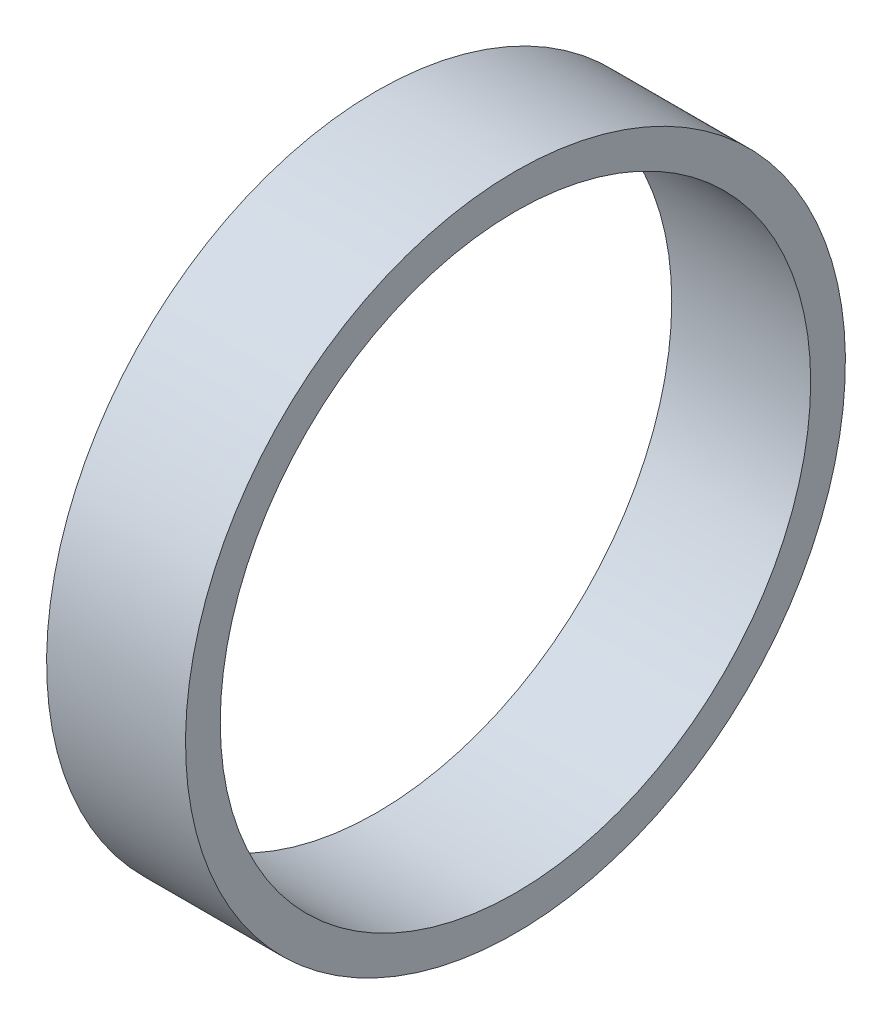
SolidWorks part; units mm, degrees
ref_plane "Front Plane" through (0, 0, 0) normal (0, 0, 1) x (1, 0, 0)
ref_plane "Top Plane" through (0, 0, 0) normal (0, 1, 0) x (1, 0, 0)
ref_plane "Right Plane" through (0, 0, 0) normal (1, 0, 0) x (0, 0, -1)
sketch "Sketch1" plane through (0, 0, 0) normal (0, 0, 1) x (1, 0, 0)
  line L0 (0, 0) -> (2000, 0) construction
  line L1 (1100, 170) -> (1100, 190)
  line L2 (1100, 190) -> (1180, 190)
  line L3 (1180, 190) -> (1180, 170)
  line L4 (1180, 170) -> (1100, 170)
revolve "Revolve1" add sketch "Sketch1" angle 360 about L0
